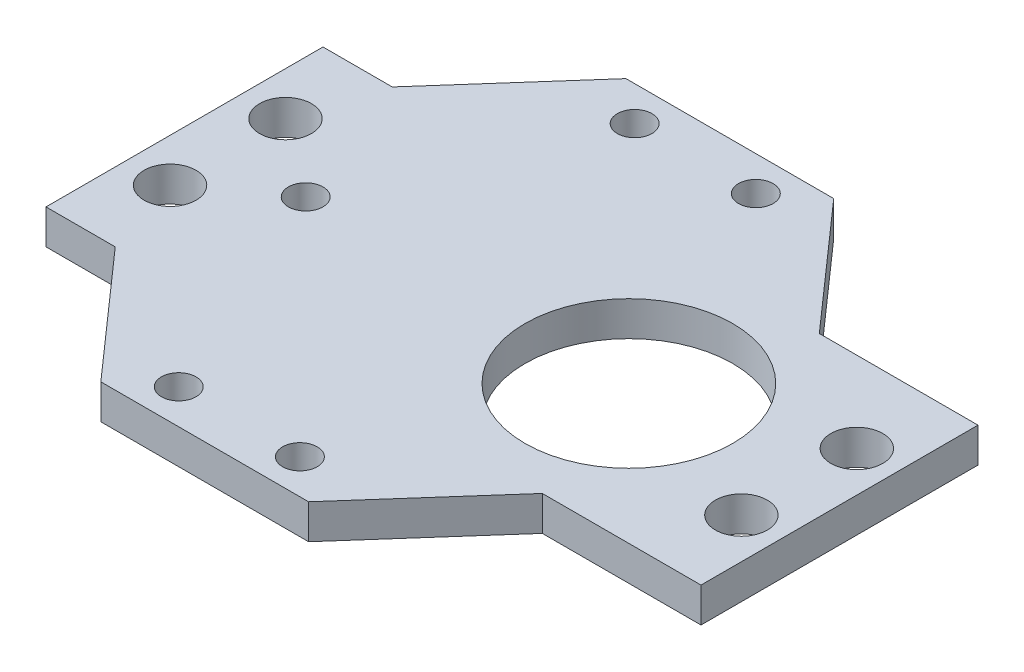
SolidWorks part; units mm, degrees
ref_plane "Front Plane" through (0, 0, 0) normal (0, 0, 1) x (1, 0, 0)
ref_plane "Top Plane" through (0, 0, 0) normal (0, 1, 0) x (1, 0, 0)
ref_plane "Right Plane" through (0, 0, 0) normal (1, 0, 0) x (0, 0, -1)
sketch "Sketch1" plane through (0, 0, 0) normal (0, 1, 0) x (1, 0, 0)
  line L0 (9, 0) -> (-9, 0)
  line L1 (-9, 0) -> (-18.5, 10.75)
  line L2 (-18.5, 10.75) -> (-24.5, 10.75)
  line L3 (-24.5, 10.75) -> (-24.5, 34.75)
  line L4 (-24.5, 34.75) -> (-18.5, 34.75)
  line L5 (-18.5, 34.75) -> (-18.5, 10.75) construction
  line L6 (-18.5, 34.75) -> (-9, 45.5)
  line L7 (-9, 45.5) -> (9, 45.5)
  line L8 (0, 45.5) -> (0, 0) construction
  line L9 (-24.5, 22.75) -> (0, 22.75) construction
  line L10 (-9, 45.5) -> (-9, 0) construction
  line L11 (18.5, 34.75) -> (9, 45.5)
  line L12 (9, 0) -> (18.5, 10.75)
  line L13 (18.5, 34.75) -> (32.25, 34.75)
  line L14 (32.25, 34.75) -> (32.25, 10.75)
  line L15 (32.25, 10.75) -> (18.5, 10.75)
  dimension "D1" = 9
  dimension "D2" = 24
  dimension "D3" = 6
  dimension "D4" = 45.5
  dimension "D5" = 24.5
  dimension "D6" = 32.25
extrude "Boss-Extrude1" add sketch "Sketch1" along normal blind 3
sketch "Sketch2" plane through (0, 3, 0) normal (0, 1, 0) x (1, 0, 0)
  line L0 (14, 35) -> (14, 22.75) construction
  line L1 (19, 17.75) -> (9, 17.75) construction
  line L2 (19, 17.75) -> (19, 27.75) construction
  line L3 (19, 27.75) -> (9, 27.75) construction
  line L4 (9, 17.75) -> (9, 27.75) construction
  line L5 (19, 17.75) -> (9, 27.75) construction
  line L6 (19, 27.75) -> (9, 17.75) construction
  line L7 (14, 22.75) -> (26.77, 22.75) construction
  line L8 (-24.5, 22.75) -> (14, 22.75) construction
  line L9 (-24.5, 34.75) -> (-24.5, 10.75) construction
  line L10 (0, 0) -> (0, 45.5) construction
  line L11 (9, 45.5) -> (-9, 45.5) construction
  circle A0 centre (14, 22.75) radius 9
  circle A1 centre (9, 27.75) radius 1 construction
  circle A2 centre (19, 27.75) radius 1 construction
  circle A3 centre (19, 17.75) radius 1 construction
  circle A4 centre (9, 17.75) radius 1 construction
  circle A5 centre (14, 22.75) radius 7.0711 construction
  circle A6 centre (6.9289, 22.75) radius 1 construction
  circle A7 centre (14, 15.6789) radius 1 construction
  circle A8 centre (21.0711, 22.75) radius 1 construction
  circle A9 centre (14, 29.8211) radius 1 construction
  circle A10 centre (-14, 22.75) radius 9 construction
  circle A11 centre (-14, 22.75) radius 1.5
  dimension "D1" = 18
  dimension "D3" = 2
  dimension "D2" = 45
  dimension "D4" = 10
  dimension "D5" = 12.77
  dimension "D6" = 14
extrude "Cut-Extrude1" cut sketch "Sketch2" against normal blind 3
sketch "Sketch3" plane through (0, 0, 0) normal (0, 1, 0) x (1, 0, 0)
  line L0 (-5.25, 42.5) -> (5.25, 42.5) construction
  line L1 (0, 42.5) -> (0, 0) construction
  line L2 (-9, 0) -> (9, 0) construction
  line L3 (9, 45.5) -> (-9, 45.5) construction
  line L4 (-24.5, 22.75) -> (32.25, 22.75) construction
  line L5 (-24.5, 34.75) -> (-24.5, 10.75) construction
  line L6 (32.25, 10.75) -> (32.25, 34.75) construction
  circle A0 centre (-5.25, 42.5) radius 1.5
  circle A1 centre (5.25, 42.5) radius 1.5
  circle A2 centre (5.25, 3) radius 1.5
  circle A3 centre (-5.25, 3) radius 1.5
  dimension "D1" = 10.5
  dimension "D2" = 3
extrude "Cut-Extrude2" cut sketch "Sketch3" along normal blind 12
sketch "Sketch4" plane through (0, 0, 0) normal (0, 1, 0) x (1, 0, 0)
  line L0 (-24.5, 22.75) -> (-20.75, 22.75) construction
  line L1 (-20.75, 17.75) -> (28.7495, 17.75) construction
  line L2 (-20.75, 17.75) -> (-20.75, 27.75) construction
  line L3 (-20.75, 27.75) -> (28.7495, 27.75) construction
  line L4 (28.7495, 17.75) -> (28.7495, 27.75) construction
  line L5 (-24.5, 34.75) -> (-24.5, 10.75) construction
  circle A0 centre (14, 22.75) radius 9 construction
  circle A1 centre (-20.75, 27.75) radius 2.25
  circle A2 centre (-20.75, 17.75) radius 2.25
  circle A3 centre (28.7495, 17.75) radius 2.25
  circle A4 centre (28.7495, 27.75) radius 2.25
  dimension "D3" = 14.7495
  dimension "D1" = 10
  dimension "D2" = 49.4995
extrude "Cut-Extrude3" cut sketch "Sketch4" along normal blind 27
sketch "Sketch5" plane through (0, 0, -45.5) normal (0, 0, -1) x (-1, 0, 0)
  line L0 (0, 3) -> (0, 0) construction
  line L1 (-9, 3) -> (9, 3) construction
  circle A0 centre (0, 1.5) radius 0.6194
  point P6 (0, 1.5)
extrude "Cut-Extrude4" cut sketch "Sketch5" against normal blind 1
